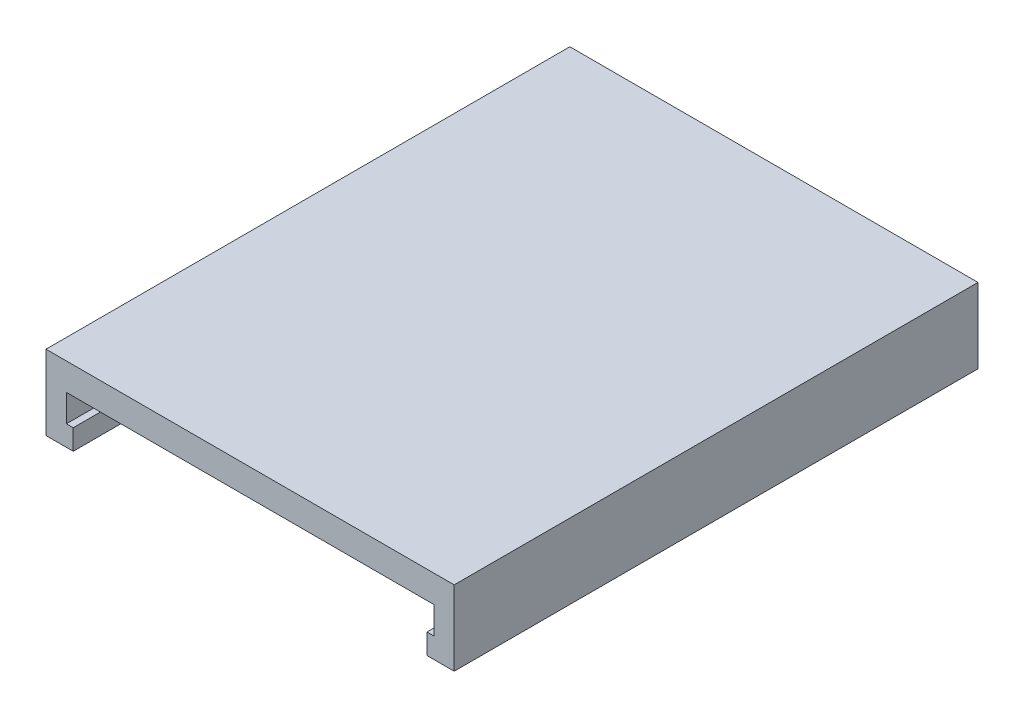
SolidWorks part; units mm, degrees
ref_plane "정면" through (0, 0, 0) normal (0, 0, 1) x (1, 0, 0)
ref_plane "윗면" through (0, 0, 0) normal (0, 1, 0) x (1, 0, 0)
ref_plane "우측면" through (0, 0, 0) normal (1, 0, 0) x (0, 0, -1)
sketch "스케치1" plane through (0, 0, 0) normal (0, 0, 1) x (1, 0, 0)
  line L1 (0, 0) -> (54, 0)
  line L2 (0, 0) -> (0, 4)
  line L3 (0, 4) -> (54, 4)
  line L4 (54, 0) -> (54, 4)
  line L5 (-3, 0) -> (57, 0)
  line L6 (-3, 0) -> (-3, 8)
  line L7 (-3, 8) -> (57, 8)
  line L8 (57, 0) -> (57, 8)
  dimension "D1" = 4
  dimension "D2" = 8
  dimension "D3" = 3
  dimension "D4" = 3
  dimension "D5" = 54
extrude "보스-돌출1" add sketch "스케치1" along normal blind 72 contours L5 L8 L7 L6 L2 L3 L4
sketch "스케치2" plane through (0, 0, 0) normal (0, -1, 0) x (1, 0, 0)
  line L0 (0, 0) -> (54, 0) construction
  line L1 (-3, 72) -> (1, 72)
  line L2 (-3, 72) -> (-3, 0)
  line L3 (-3, 0) -> (1, 0)
  line L4 (1, 72) -> (1, 0)
  line L5 (0, 72) -> (54, 72) construction
  line L6 (57, 0) -> (53, 0)
  line L7 (57, 0) -> (57, 72)
  line L8 (57, 72) -> (53, 72)
  line L9 (53, 0) -> (53, 72)
  dimension "D1" = 4
  dimension "D2" = 4
extrude "보스-돌출2" add sketch "스케치2" along normal blind 3
sketch "스케치4" plane through (0, 0, 0) normal (0, 0, -1) x (-1, 0, 0)
  line L1 (-57, 8) -> (3, 8)
  line L2 (-57, 8) -> (-57, -3)
  line L3 (-57, -3) -> (3, -3)
  line L4 (3, 8) -> (3, -3)
extrude "보스-돌출3" add sketch "스케치4" along normal blind 5
